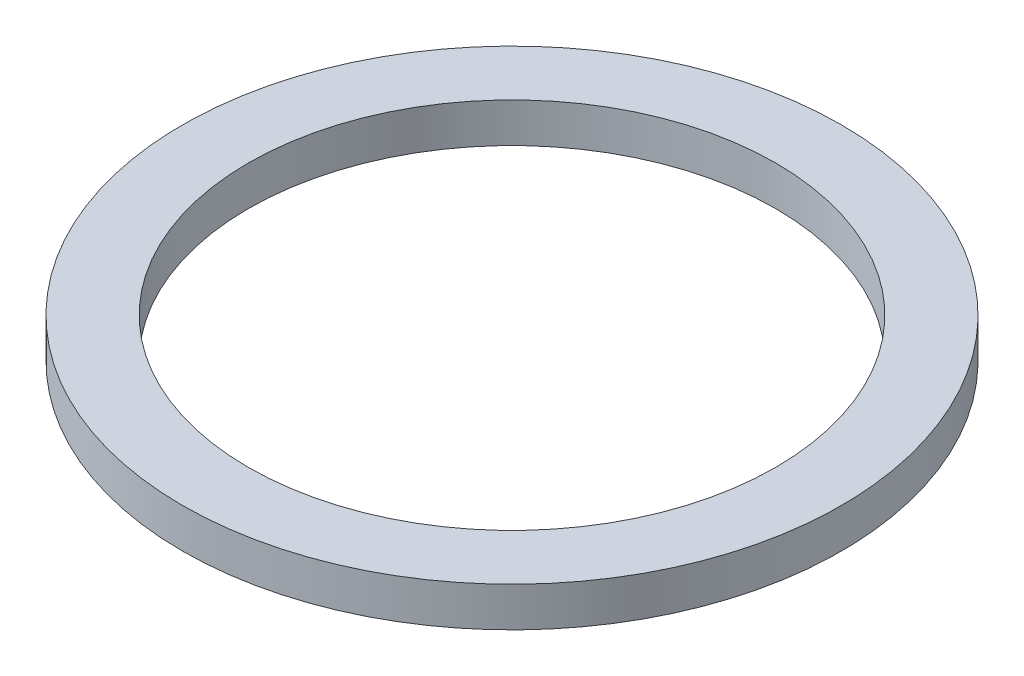
SolidWorks part; units mm, degrees
ref_plane "Front Plane" through (0, 0, 0) normal (0, 0, 1) x (1, 0, 0)
ref_plane "Top Plane" through (0, 0, 0) normal (0, 1, 0) x (1, 0, 0)
ref_plane "Right Plane" through (0, 0, 0) normal (1, 0, 0) x (0, 0, -1)
sketch "Sketch1" plane through (0, 0, 0) normal (0, 1, 0) x (1, 0, 0)
  circle A0 centre (0, 0) radius 20
  circle A1 centre (0, 0) radius 25
  dimension "D1" = 50
  dimension "D2" = 40
extrude "Boss-Extrude1" add sketch "Sketch1" along normal blind 3
equation "\"Outer Diameter\"= 50mm"
equation "\"Inner Diameter\"= 40mm"
equation "\"D1@Sketch1\"=\"Outer Diameter\""
equation "\"D2@Sketch1\"=\"Inner Diameter\""
equation "\"Thickness gasket\"= 3mm"
equation "\"D1@Boss-Extrude1\"=\"Thickness gasket\""
